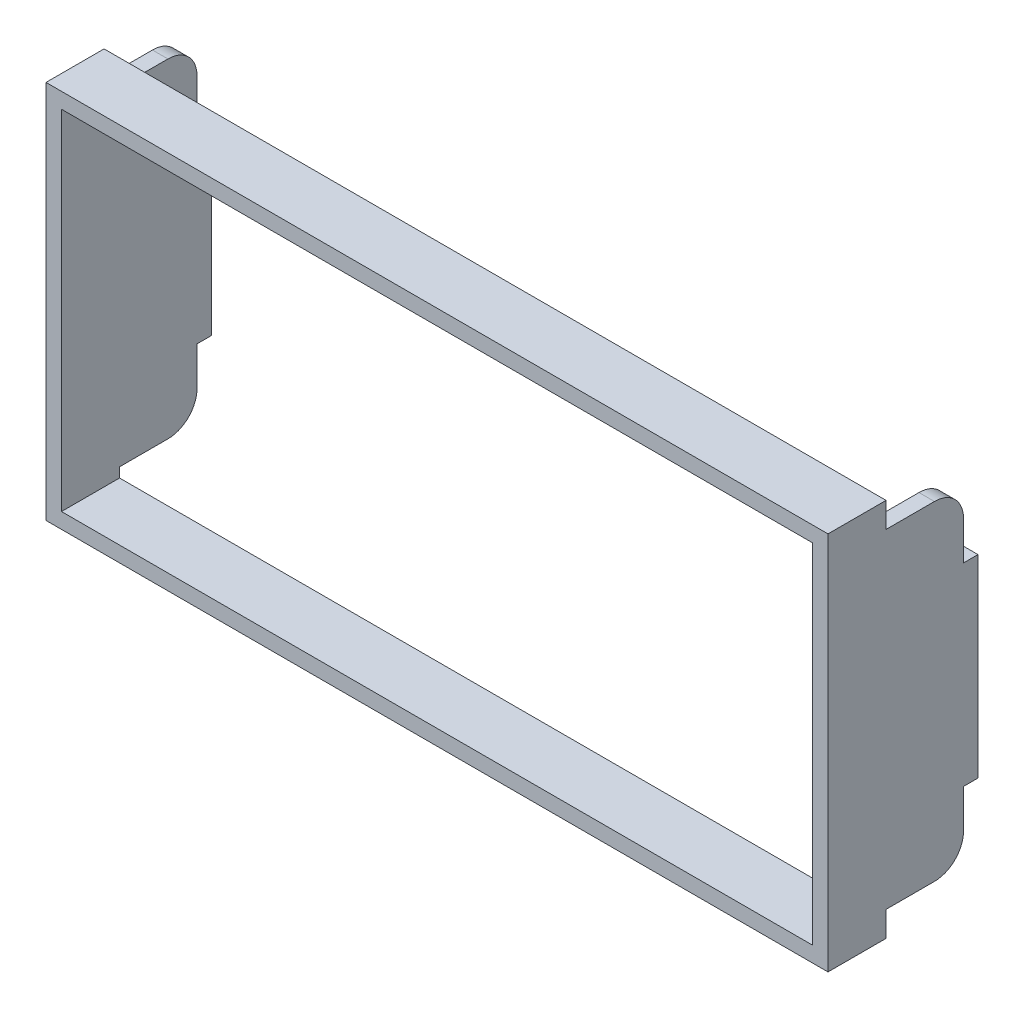
SolidWorks part; units mm, degrees
ref_plane "Front Plane" through (0, 0, 0) normal (0, 0, 1) x (1, 0, 0)
ref_plane "Top Plane" through (0, 0, 0) normal (0, 1, 0) x (1, 0, 0)
ref_plane "Right Plane" through (0, 0, 0) normal (1, 0, 0) x (0, 0, -1)
sketch "Sketch1" plane through (0, 0, 0) normal (0, 0, 1) x (1, 0, 0)
  line L0 (0, 0) -> (0, -36)
  line L1 (0, -36) -> (77.6, -36)
  line L2 (77.6, -36) -> (77.6, 0)
  line L3 (77.6, 0) -> (0, 0)
  line L4 (79.2, 1.6) -> (-1.6, 1.6)
  line L5 (-1.6, 1.6) -> (-1.6, -37.6)
  line L6 (-1.6, -37.6) -> (79.2, -37.6)
  line L7 (79.2, -37.6) -> (79.2, 1.6)
  dimension "D1" = 36
  dimension "D2" = 77.6
  dimension "D3" = 1.6
extrude "Boss-Extrude1" add sketch "Sketch1" along normal blind 6
sketch "Sketch2" plane through (0, 0, 0) normal (0, 0, -1) x (-1, 0, 0)
  line L0 (-77.6, 0) -> (-79.2, 0)
  line L1 (-79.2, -37.6) -> (-79.2, 1.6) construction
  line L2 (-77.6, -36) -> (-79.2, -36)
  line L3 (-79.2, -36) -> (-79.2, 0)
  line L4 (-77.6, 0) -> (-77.6, -36)
  line L5 (-38.8, 0) -> (-38.8, -36) construction
  line L6 (-77.6, 0) -> (0, 0) construction
  line L7 (0, -36) -> (-77.6, -36) construction
  line L8 (0, 0) -> (0, -36)
  line L9 (1.6, -36) -> (1.6, 0)
  line L10 (0, -36) -> (1.6, -36)
  line L11 (0, 0) -> (1.6, 0)
extrude "Boss-Extrude2" add sketch "Sketch2" along normal blind 8
other "Move Face1" face at (78.4, 0, -4) face at (78.4, -36, -4) face at (-0.8, -36, -4) face at (-0.8, 0, -4) parameters "D1"=1
ref_plane "Plane1" through (38.8, 0, 0) normal (-1, 0, 0) x (0, 0, 1)
ref_plane "Plane2" through (0, -18, 0) normal (0, -1, 0) x (-1, 0, 0)
sketch "Sketch3" plane through (0, 0, -8) normal (0, 0, -1) x (-1, 0, 0)
  line L0 (-79.2, -28) -> (-79.2, -8)
  line L1 (-79.2, -1) -> (-79.2, -35) construction
  line L2 (-79.2, -8) -> (-77.6, -8)
  line L3 (-77.6, -35) -> (-77.6, -1) construction
  line L4 (-77.6, -8) -> (-77.6, -28)
  line L5 (-77.6, -28) -> (-79.2, -28)
  line L6 (-38.8, 0) -> (-38.8, -36.144) construction
  line L7 (-77.6, 0) -> (0, 0) construction
  line L8 (-38.8, -7.7) -> (-38.8, 7.7) construction
  line L9 (0, -28) -> (1.6, -28)
  line L10 (0, -8) -> (0, -28)
  line L11 (1.6, -8) -> (0, -8)
  line L12 (1.6, -28) -> (1.6, -8)
  point P5 (-79.2, -18)
  point P6 (-79.2, -18)
  dimension "D1" = 20
extrude "Boss-Extrude3" add sketch "Sketch3" along normal blind 2
chamfer "Chamfer1" distance 0.5 angle 45 8 edges at (-0.8, -8, -10) (-1.6, -18, -10) (-0.8, -28, -10) (0, -18, -10) (79.2, -18, -10) (78.4, -8, -10) (77.6, -18, -10) (78.4, -28, -10)
fillet "Fillet1" radius 3 4 edges at (-0.8, -1, -8) (-0.8, -35, -8) (78.4, -35, -8) (78.4, -1, -8)
